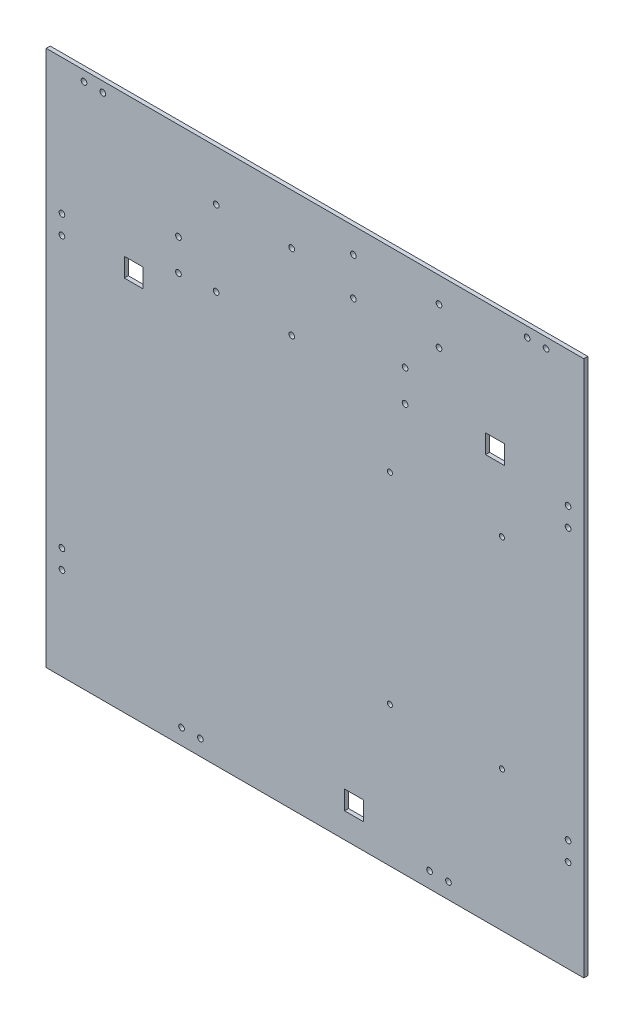
SolidWorks part; units mm, degrees
material "6061-O (SS)"
ref_plane "Front Plane" through (0, 0, 0) normal (0, 0, 1) x (1, 0, 0)
ref_plane "Top Plane" through (0, 0, 0) normal (0, 1, 0) x (1, 0, 0)
ref_plane "Right Plane" through (0, 0, 0) normal (1, 0, 0) x (0, 0, -1)
sketch "Sketch1" plane through (0, 0, 0) normal (0, 0, 1) x (1, 0, 0)
  line L1 (0, 0) -> (427, 0)
  line L2 (0, 0) -> (0, 426)
  line L3 (0, 426) -> (427, 426)
  line L4 (427, 0) -> (427, 426)
  dimension "D1" = 427
  dimension "D2" = 426
extrude "Boss-Extrude1" add sketch "Sketch1" along normal blind 3.175
sketch "Sketch2" plane through (0, 0, 3.175) normal (0, 0, 1) x (1, 0, 0)
  line L0 (213.5, 426) -> (213.5, 160.9876) construction
  line L1 (427, 426) -> (0, 426) construction
  circle A0 centre (12.5, 318.5) radius 2.25
  circle A1 centre (12.5, 303.5) radius 2.25
  circle A2 centre (12.5, 88.5) radius 2.25
  circle A3 centre (12.5, 73.5) radius 2.25
  circle A4 centre (414.5, 88.5) radius 2.25
  circle A5 centre (414.5, 73.5) radius 2.25
  circle A6 centre (414.5, 318.5) radius 2.25
  circle A7 centre (414.5, 303.5) radius 2.25
  dimension "D3" = 4.5
  dimension "D1" = 15
  dimension "D2" = 15
extrude "Cut-Extrude1" cut sketch "Sketch2" against normal through all
sketch "Sketch3" plane through (0, 0, 3.175) normal (0, 0, 1) x (1, 0, 0)
  line L0 (0, 0) -> (427, 0) construction
  line L1 (427, 0) -> (427, 426) construction
  circle A0 centre (304.5, 12.5) radius 2.25
  circle A1 centre (319.5, 12.5) radius 2.25
  circle A2 centre (122.5, 12.5) radius 2.25
  circle A3 centre (107.5, 12.5) radius 2.25
  dimension "D4" = 4.5
  dimension "D1" = 15
  dimension "D2" = 12.5
  dimension "D3" = 107.5
  dimension "D5" = 15
  dimension "D6" = 12.5
  dimension "D7" = 107.5
extrude "Cut-Extrude2" cut sketch "Sketch3" against normal through all
sketch "Sketch4" plane through (0, 0, 3.175) normal (0, 0, 1) x (1, 0, 0)
  line L0 (0, 0) -> (427, 0) construction
  line L1 (237, 20) -> (252, 20)
  line L2 (237, 20) -> (237, 35)
  line L3 (237, 35) -> (252, 35)
  line L4 (252, 20) -> (252, 35)
  line L5 (427, 0) -> (427, 426) construction
  line L6 (0, 426) -> (0, 0) construction
  line L7 (349, 336) -> (364, 336)
  line L8 (62, 314) -> (77, 314)
  line L9 (62, 314) -> (62, 299)
  line L10 (62, 299) -> (77, 299)
  line L11 (77, 314) -> (77, 299)
  line L12 (349, 336) -> (349, 321)
  line L13 (349, 321) -> (364, 321)
  line L14 (364, 336) -> (364, 321)
  line L15 (427, 426) -> (0, 426) construction
  dimension "D1" = 20
  dimension "D2" = 15
  dimension "D3" = 15
  dimension "D4" = 175
  dimension "D5" = 15
  dimension "D6" = 15
  dimension "D7" = 15
  dimension "D8" = 15
  dimension "D9" = 62
  dimension "D10" = 112
  dimension "D11" = 90
  dimension "D12" = 63
extrude "Cut-Extrude3" cut sketch "Sketch4" against normal through all
sketch "Sketch5" plane through (0, 0, 0) normal (0, 0, -1) x (-1, 0, 0)
  line L0 (-427, 426) -> (0, 426) construction
  line L1 (-427, 0) -> (-427, 426) construction
  circle A0 centre (-362, 271) radius 2
  circle A1 centre (-273, 271) radius 2
  circle A2 centre (-362, 111.3) radius 2
  circle A3 centre (-273, 111.3) radius 2
  dimension "D3" = 4
  dimension "D1" = 89
  dimension "D2" = 159.7
  dimension "D4" = 155
  dimension "D5" = 65
extrude "Cut-Extrude4" cut sketch "Sketch5" against normal through all
sketch "Sketch6" plane through (0, 0, 0) normal (0, 0, -1) x (-1, 0, 0)
  line L0 (-427, 426) -> (0, 426) construction
  line L1 (0, 426) -> (0, 0) construction
  circle A0 centre (-195, 386) radius 2.25
  circle A1 centre (-135, 386) radius 2.25
  circle A2 centre (-195, 326) radius 2.25
  circle A3 centre (-135, 326) radius 2.25
  dimension "D5" = 4.5
  dimension "D1" = 60
  dimension "D2" = 60
  dimension "D3" = 40
  dimension "D4" = 135
extrude "Cut-Extrude5" cut sketch "Sketch6" against normal through all
sketch "Sketch7" plane through (0, 0, 0) normal (0, 0, -1) x (-1, 0, 0)
  line L0 (-427, 426) -> (0, 426) construction
  line L1 (-427, 0) -> (-427, 426) construction
  line L2 (-312, 391) -> (-244, 391) construction
  circle A0 centre (-312, 406) radius 2.25
  circle A1 centre (-244, 406) radius 2.25
  circle A2 centre (-244, 376) radius 2.25
  circle A3 centre (-312, 376) radius 2.25
  dimension "D2" = 4.5
  dimension "D1" = 20
  dimension "D3" = 115
  dimension "D4" = 68
  dimension "D5" = 30
extrude "Cut-Extrude6" cut sketch "Sketch7" against normal through all
sketch "Sketch8" plane through (0, 0, 3.175) normal (0, 0, 1) x (1, 0, 0)
  line L0 (427, 426) -> (0, 426) construction
  line L1 (0, 426) -> (0, 0) construction
  line L2 (427, 0) -> (427, 426) construction
  circle A0 centre (285.04, 348.92) radius 2.25
  circle A1 centre (105.04, 348.92) radius 2.25
  circle A2 centre (105.04, 323.92) radius 2.25
  circle A3 centre (285.04, 323.92) radius 2.25
  point P12 (0, 0)
  point P17 (0, 0)
  point P18 (0, 0)
  point P19 (0, 0)
  point P22 (0, 0)
  point P23 (0, 0)
  point P24 (0, 0)
  dimension "D1" = 4.5
  dimension "D2" = 77.08
  dimension "D3" = 105.04
  dimension "D4" = 25
  dimension "D5" = 141.96
  dimension "D6" = 25
extrude "Cut-Extrude7" cut sketch "Sketch8" against normal blind 10
sketch "Sketch9" plane through (0, 0, 0) normal (0, 0, -1) x (-1, 0, 0)
  line L0 (0, 426) -> (0, 0) construction
  line L1 (-427, 0) -> (-427, 426) construction
  line L2 (-427, 426) -> (0, 426) construction
  circle A0 centre (-30, 418) radius 2.25
  circle A1 centre (-397, 418) radius 2.25
  circle A2 centre (-382, 418) radius 2.25
  circle A3 centre (-45, 418) radius 2.25
  dimension "D1" = 4.5
  dimension "D2" = 30
  dimension "D3" = 30
  dimension "D4" = 8
  dimension "D5" = 15
  dimension "D6" = 15
extrude "Cut-Extrude8" cut sketch "Sketch9" against normal blind 10
